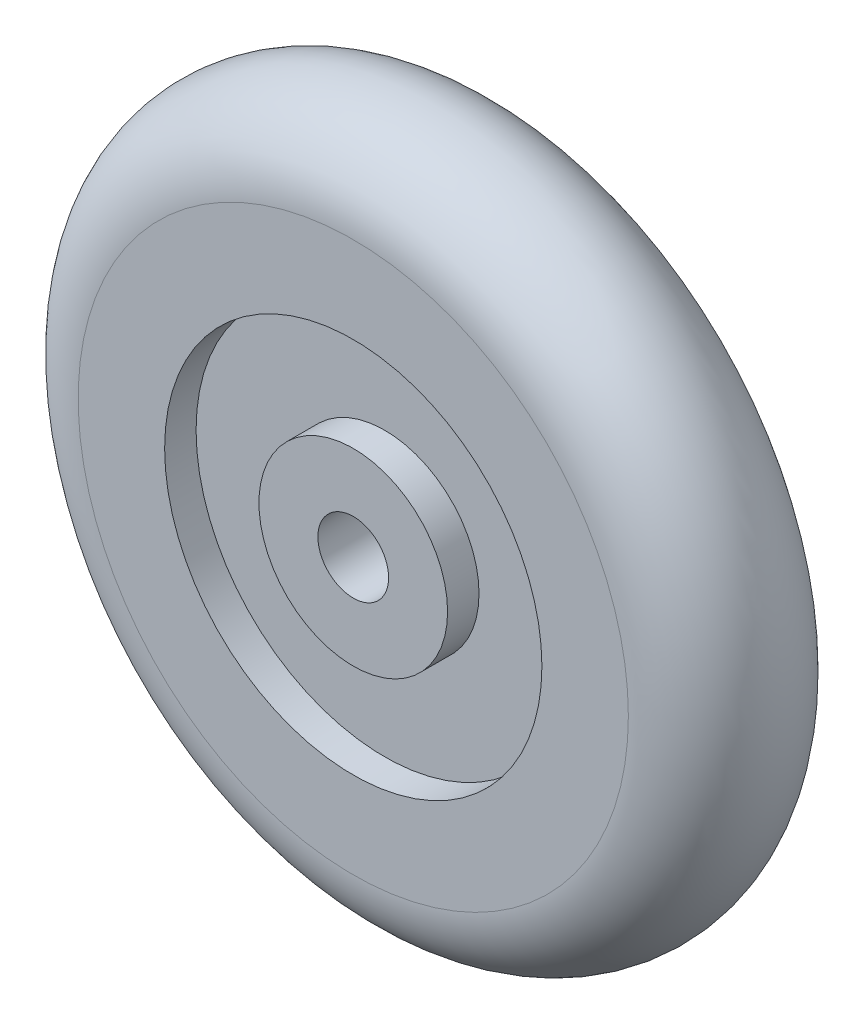
SolidWorks part; units mm, degrees
material "Oak"
ref_plane "Front" through (0, 0, 0) normal (0, 0, 1) x (1, 0, 0)
ref_plane "Top" through (0, 0, 0) normal (0, 1, 0) x (1, 0, 0)
ref_plane "Right" through (0, 0, 0) normal (1, 0, 0) x (0, 0, -1)
sketch "Sketch1" plane through (0, 0, 0) normal (1, 0, 0) x (0, 0, -1)
  line L0 (0, 0) -> (0, -22.5)
  line L1 (-5, -6) -> (-5, 0)
  line L2 (-5, 0) -> (0, 0) construction
  line L3 (-5, -6) -> (-3, -6)
  line L4 (-3, -6) -> (-3, -12)
  line L5 (-3, -12) -> (-5, -12)
  line L6 (-5, -12) -> (-5, -17.5)
  line L7 (0, 0) -> (-5, 0)
  arc A0 (-5, -17.5) -> (0, -22.5) centre (0, -17.5) ccw
  dimension "D2" = 5
  dimension "D1" = 17.5
  dimension "D3" = 6
  dimension "D4" = 12
  dimension "D5" = 2
revolve "Revolve1" add sketch "Sketch1" angle 360 about L2
mirror "Mirror1" about plane through (0, 0, 0) normal (0, 0, 1) of "Revolve1"
sketch "Sketch3" plane through (0, 0, -5) normal (0, 0, -1) x (-1, 0, 0)
  circle A0 centre (0, 0) radius 2.25
  dimension "D1" = 4.5
extrude "Cut-Extrude2" cut sketch "Sketch3" against normal through all
